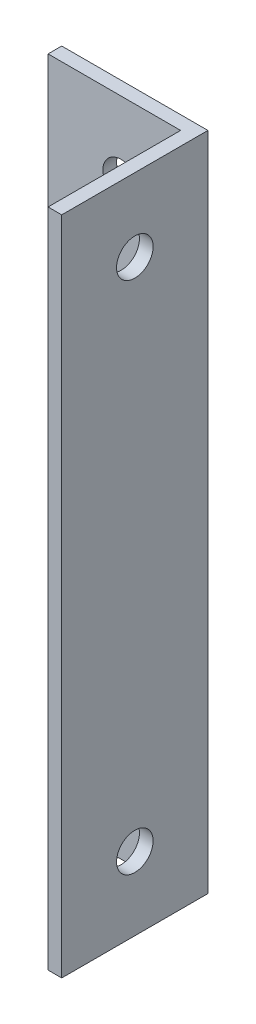
SolidWorks part; units mm, degrees
ref_plane "Front Plane" through (0, 0, 0) normal (0, 0, 1) x (1, 0, 0)
ref_plane "Top Plane" through (0, 0, 0) normal (0, 1, 0) x (1, 0, 0)
ref_plane "Right Plane" through (0, 0, 0) normal (1, 0, 0) x (0, 0, -1)
sketch "Sketch1" plane through (0, 0, 0) normal (0, 1, 0) x (1, 0, 0)
  line L0 (0, 0) -> (0, 19.05)
  line L1 (0, 19.05) -> (-19.05, 19.05)
  line L2 (-19.05, 19.05) -> (-19.05, 17.272)
  line L3 (-19.05, 17.272) -> (-1.778, 17.272)
  line L4 (-1.778, 17.272) -> (-1.778, 0)
  line L5 (-1.778, 0) -> (0, 0)
  dimension "D1" = 1.778
  dimension "D2" = 1.778
  dimension "D3" = 19.05
  dimension "D4" = 19.05
extrude "Boss-Extrude1" add sketch "Sketch1" along normal blind 86.106
sketch "Sketch2" plane through (-1.778, 0, 0) normal (-1, 0, 0) x (0, 0, 1)
  line L0 (0, 86.106) -> (0, 0) construction
  line L1 (-17.272, 0) -> (0, 0) construction
  line L2 (-17.272, 86.106) -> (0, 86.106) construction
  circle A0 centre (-9.525, 76.581) radius 2.3812
  circle A1 centre (-9.525, 9.525) radius 2.3813
  dimension "D1" = 4.7625
  dimension "D2" = 4.7625
  dimension "D6" = 9.525
  dimension "D3" = 9.525
  dimension "D4" = 9.525
  dimension "D5" = 9.525
extrude "Cut-Extrude1" cut sketch "Sketch2" against normal up to surface (1.778 mm away) up to face at (0, 43.053, -9.525)
sketch "Sketch3" plane through (0, 0, -17.272) normal (0, 0, 1) x (1, 0, 0)
  line L0 (-19.05, 86.106) -> (-1.778, 86.106) construction
  line L1 (-19.05, 86.106) -> (-19.05, 0) construction
  line L2 (-19.05, 0) -> (-1.778, 0) construction
  circle A0 centre (-9.525, 9.525) radius 2.3813
  circle A1 centre (-9.525, 76.581) radius 2.3812
  dimension "D1" = 4.7625
  dimension "D2" = 4.7625
  dimension "D3" = 9.525
  dimension "D4" = 9.525
  dimension "D5" = 9.525
  dimension "D6" = 9.525
extrude "Cut-Extrude2" cut sketch "Sketch3" against normal up to surface (1.778 mm away) up to face at (-9.525, 43.053, -19.05)
